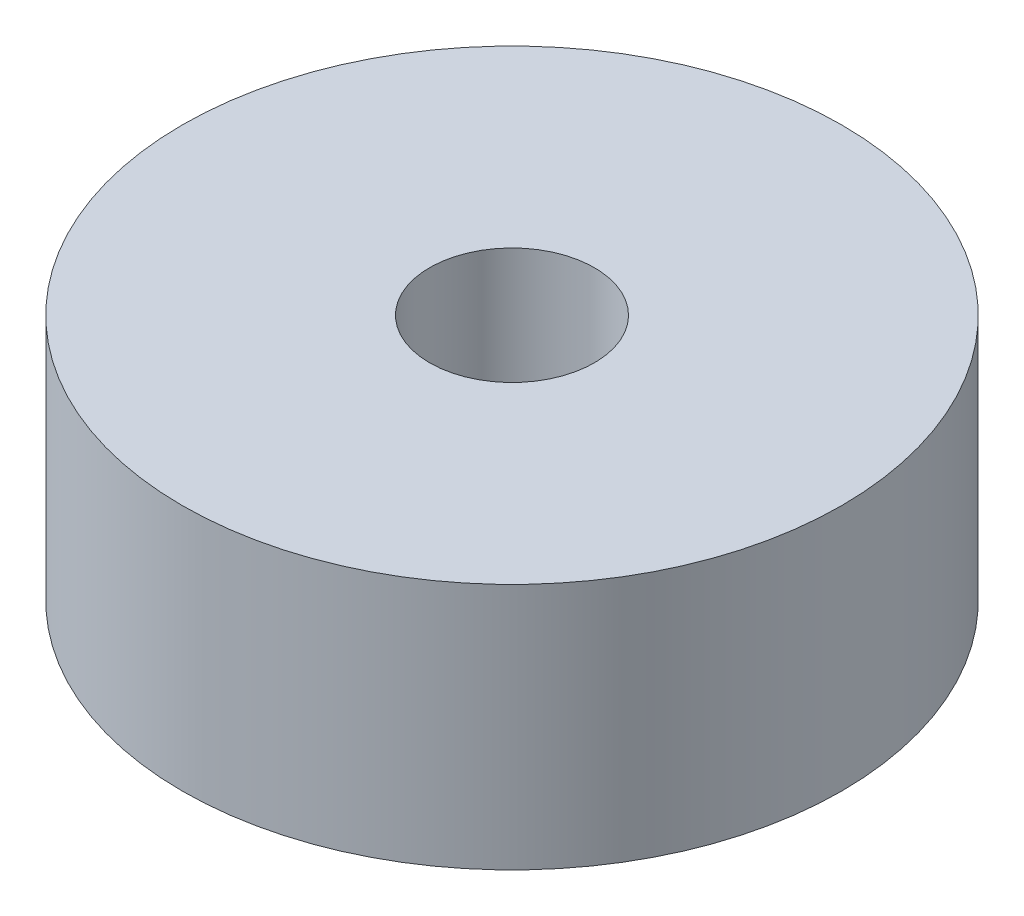
SolidWorks part; units mm, degrees
material "AISI 304"
ref_plane "前视基准面" through (0, 0, 0) normal (0, 0, 1) x (1, 0, 0)
ref_plane "上视基准面" through (0, 0, 0) normal (0, 1, 0) x (1, 0, 0)
ref_plane "右视基准面" through (0, 0, 0) normal (1, 0, 0) x (0, 0, -1)
other "Configuration Table"
sketch "草图1" plane through (0, 0, 0) normal (0, 1, 0) x (1, 0, 0)
  circle A0 centre (0, 0) radius 1
  circle A1 centre (0, 0) radius 4
  dimension "D1" = 2
  dimension "D2" = 8
extrude "凸台-拉伸1" add sketch "草图1" along normal blind 3
